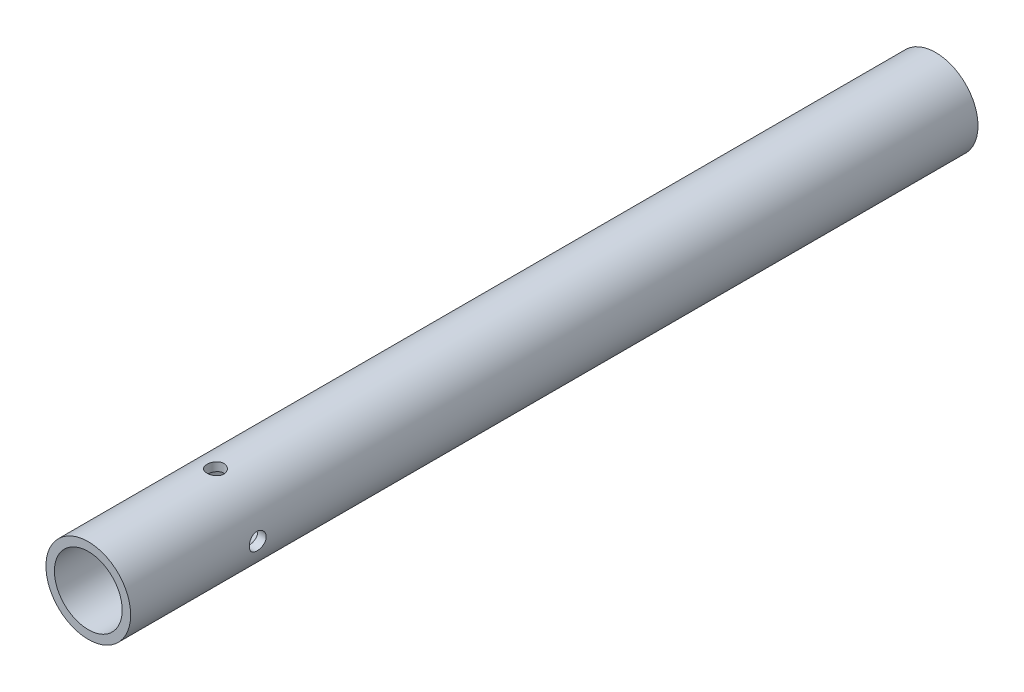
SolidWorks part; units mm, degrees
ref_plane "Front Plane" through (0, 0, 0) normal (0, 0, 1) x (1, 0, 0)
ref_plane "Top Plane" through (0, 0, 0) normal (0, 1, 0) x (1, 0, 0)
ref_plane "Right Plane" through (0, 0, 0) normal (1, 0, 0) x (0, 0, -1)
sketch "Sketch1" plane through (0, 0, 0) normal (0, 0, 1) x (1, 0, 0)
  circle A0 centre (0, 0) radius 500
  circle A1 centre (0, 0) radius 400
  dimension "D1" = 800
  dimension "D2" = 1000
extrude "Boss-Extrude1" add sketch "Sketch1" along normal blind 10000
sketch "Sketch2" plane through (0, 0, 0) normal (0, 1, 0) x (1, 0, 0)
  line L0 (-500, -10000) -> (500, -10000) construction
  circle A0 centre (0, -8500) radius 100
  dimension "D1" = 1500
extrude "Cut-Extrude1" cut sketch "Sketch2" against normal through all and the other way through all
sketch "Sketch3" plane through (0, 0, 0) normal (1, 0, 0) x (0, 0, -1)
  line L0 (-10000, 500) -> (-10000, -500) construction
  circle A0 centre (-8500, 0) radius 100
  dimension "D1" = 1500
extrude "Cut-Extrude2" cut sketch "Sketch3" against normal through all and the other way through all
